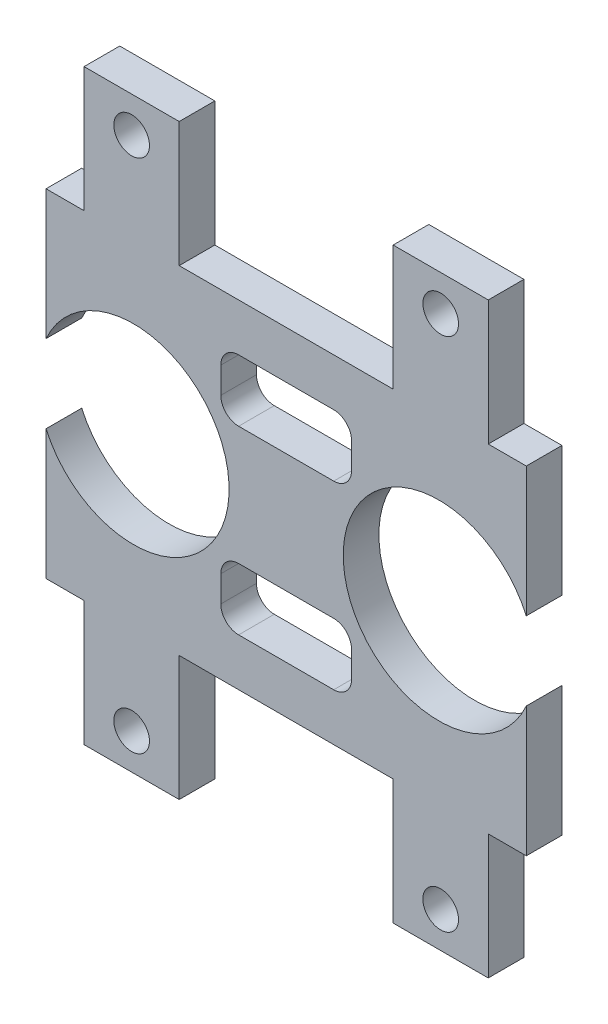
SolidWorks part; units mm, degrees
ref_plane "Plano frontal" through (0, 0, 0) normal (0, 0, 1) x (1, 0, 0)
ref_plane "Plano superior" through (0, 0, 0) normal (0, 1, 0) x (1, 0, 0)
ref_plane "Plano direito" through (0, 0, 0) normal (1, 0, 0) x (0, 0, -1)
sketch "Esboço1" plane through (0, 0, 0) normal (0, 0, 1) x (1, 0, 0)
  line L1 (20.2, -14.2) -> (-20.2, -14.2)
  line L2 (20.2, -14.2) -> (20.2, 14.2)
  line L3 (20.2, 14.2) -> (-20.2, 14.2)
  line L4 (-20.2, -14.2) -> (-20.2, 14.2)
  line L5 (20.2, -14.2) -> (-20.2, 14.2) construction
  line L6 (20.2, 14.2) -> (-20.2, -14.2) construction
  point P0 (0, 0)
  dimension "D1" = 40.4
  dimension "D2" = 28.4
extrude "Ressalto-extrusão1" add sketch "Esboço1" along normal blind 3
sketch "Esboço2" plane through (0, 0, 3) normal (0, 0, 1) x (1, 0, 0)
  line L0 (0, -18.7161) -> (0, 19.7671) construction
  line L1 (20.2, 14.2) -> (-20.2, 14.2) construction
  line L2 (20.2, 14.2) -> (-20.2, 14.2)
  line L3 (-32.7263, 0) -> (32.5829, 0) construction
  line L4 (-20.2, -14.2) -> (20.2, -14.2) construction
  line L6 (-17, -14.2) -> (-17, -24.7)
  line L7 (-17, -24.7) -> (-9, -24.7)
  line L8 (-9, -14.2) -> (-9, -24.7)
  line L9 (9, -14.2) -> (9, -24.7)
  line L10 (17, -24.7) -> (9, -24.7)
  line L11 (17, -14.2) -> (17, -24.7)
  line L12 (17, 14.2) -> (17, 24.7)
  line L13 (17, 24.7) -> (9, 24.7)
  line L14 (9, 14.2) -> (9, 24.7)
  line L15 (-9, 14.2) -> (-9, 24.7)
  line L16 (-17, 24.7) -> (-9, 24.7)
  line L17 (-17, 14.2) -> (-17, 24.7)
  line L18 (-17, 14.2) -> (-9, 14.2)
  line L19 (9, 14.2) -> (17, 14.2)
  line L20 (9, -14.2) -> (17, -14.2)
  line L21 (-17, -14.2) -> (-9, -14.2)
  circle A0 centre (-13, -21.7) radius 1.5
  circle A1 centre (-13, 21.7) radius 1.5
  circle A2 centre (13, -21.7) radius 1.5
  circle A3 centre (13, 21.7) radius 1.5
  dimension "D5" = 3
  dimension "D7" = 7.5
  dimension "D1" = 10.5
  dimension "D2" = 10.5
  dimension "D3" = 8
  dimension "D4" = 9
  dimension "D6" = 4
extrude "Ressalto-extrusão2" add sketch "Esboço2" against normal blind 3 contours L17 L2 L15 L16 | L14 L2 L12 L13 | L11 L16 L9 L10 | L8 L16 L6 L7
sketch "Esboço3" plane through (0, 0, 3) normal (0, 0, 1) x (1, 0, 0)
  line L0 (-30.8699, 0) -> (32.0662, 0) construction
  line L1 (0, 18.7898) -> (0, -18.7378) construction
  line L3 (5.5, -10.2) -> (-5.5, -10.2)
  line L5 (5.5, -5) -> (-5.5, -5)
  line L7 (-5.5, -5) -> (-5.5, -10.2)
  line L8 (5.5, -5) -> (5.5, -10.2)
  line L9 (5.5, 5) -> (-5.5, 5)
  line L10 (-5.5, 5) -> (-5.5, 10.2)
  line L11 (5.5, 10.2) -> (-5.5, 10.2)
  line L12 (5.5, 5) -> (5.5, 10.2)
  line L13 (-9, -14.2) -> (9, -14.2) construction
  circle A0 centre (-12.85, 0) radius 8.05
  circle A3 centre (12.85, 0) radius 8.05
  point P7 (0, -7.95)
  dimension "D1" = 16.1
  dimension "D2" = 12.85
  dimension "D5" = 11
  dimension "D6" = 5.5
  dimension "D3" = 5
  dimension "D4" = 4
extrude "Corte-extrusão1" cut sketch "Esboço3" against normal through all
fillet "Filete1" radius 1.5 2 edges at (-5.5, -5, 1.5) (5.5, -5, 1.5)
fillet "Filete2" radius 1.5 2 edges at (5.5, -10.2, 1.5) (-5.5, -10.2, 1.5)
fillet "Filete3" radius 1.5 4 edges at (5.5, 5, 1.5) (-5.5, 5, 1.5) (-5.5, 10.2, 1.5) (5.5, 10.2, 1.5)
